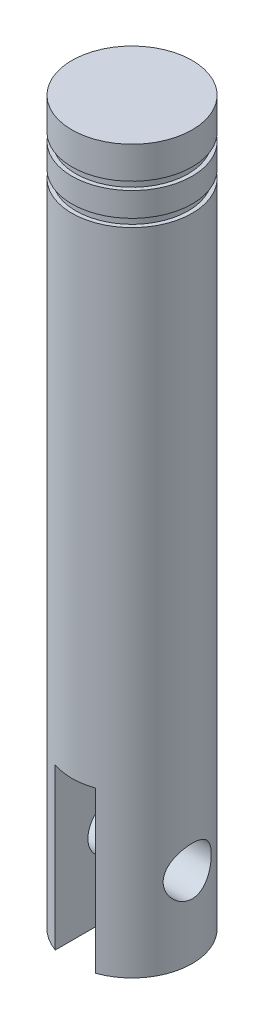
SolidWorks part; units mm, degrees
material "Messing"
ref_plane "Ebene vorne" through (0, 0, 0) normal (0, 0, 1) x (1, 0, 0)
ref_plane "Ebene oben" through (0, 0, 0) normal (0, 1, 0) x (1, 0, 0)
ref_plane "Ebene rechts" through (0, 0, 0) normal (1, 0, 0) x (0, 0, -1)
sketch "Skizze1" plane through (0, 0, 0) normal (0, 0, 1) x (1, 0, 0)
  line L0 (0, -45) -> (0, 45)
  line L1 (0, 45) -> (-7.5, 45)
  line L2 (-7.5, 45) -> (-7.5, 41)
  line L3 (-7.5, 41) -> (-7, 41)
  line L4 (-7, 41) -> (-7, 40)
  line L5 (-7, 40) -> (-7.5, 40)
  line L6 (-7.5, 40) -> (-7.5, 37)
  line L7 (-7.5, 37) -> (-7, 37)
  line L8 (-7, 37) -> (-7, 36)
  line L9 (-7, 36) -> (-7.5, 36)
  line L10 (-7.5, 36) -> (-7.5, -45)
  line L11 (-7.5, -45) -> (0, -45)
  point P4 (0, 0)
  point P7 (0, 0)
  point P16 (0, 0)
  point P17 (-6.5, 11.7014)
  dimension "D1" = 7.5
  dimension "D2" = 4
  dimension "D3" = 1
  dimension "D4" = 1
  dimension "D5" = 3
  dimension "D6" = 0.5
  dimension "D7" = 90
revolve "Rotation2" add sketch "Skizze1" angle 360 about L0
ref_plane "Ebene1" through (0, 0, 7.5) normal (0, 0, 1) x (1, 0, 0)
sketch "Skizze2" plane through (0, 0, 7.5) normal (0, 0, 1) x (1, 0, 0)
  line L0 (-7.5, -45) -> (7.5, -45) construction
  line L1 (-2.5, -45) -> (2.5, -45)
  line L2 (-2.5, -45) -> (-2.5, -25)
  line L3 (-2.5, -25) -> (2.5, -25)
  line L4 (2.5, -45) -> (2.5, -25)
  line L5 (-7.5, 36) -> (-7.5, -45) construction
  point P6 (0, -25)
  dimension "D1" = 20
  dimension "D2" = 5
  dimension "D3" = 7.5
extrude "Schnitt-Linear austragen1" cut sketch "Skizze2" against normal through all
sketch "Skizze5" plane through (0, 0, 0) normal (1, 0, 0) x (0, 0, -1)
  line L0 (-7.0711, -45) -> (7.0711, -45) construction
  circle A0 centre (0, -35) radius 3
  point P4 (0, 0)
  dimension "D1" = 6
  dimension "D2" = 10
extrude "Schnitt-Linear austragen2" cut sketch "Skizze5" against normal through all both and the other way through all
